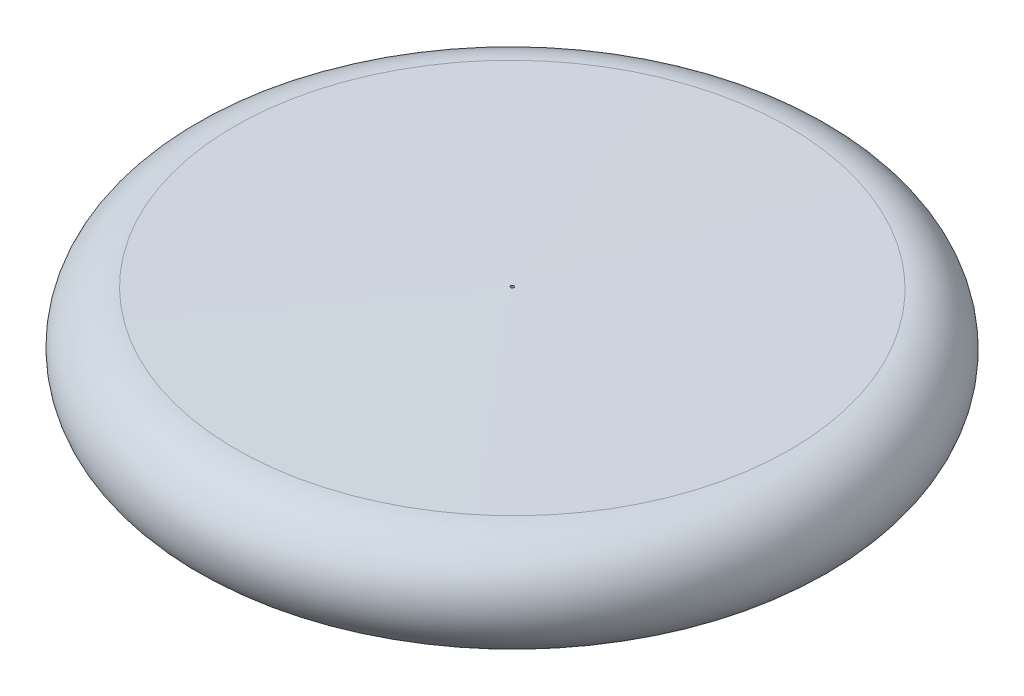
SolidWorks part; units mm, degrees
ref_plane "Front Plane" through (0, 0, 0) normal (0, 0, 1) x (1, 0, 0)
ref_plane "Top Plane" through (0, 0, 0) normal (0, 1, 0) x (1, 0, 0)
ref_plane "Right Plane" through (0, 0, 0) normal (1, 0, 0) x (0, 0, -1)
sketch "Sketch1" plane through (0, 0, 0) normal (0, 0, 1) x (1, 0, 0)
  line L0 (-2.258, 14.3692) -> (30.1083, 14.3692)
  line L1 (30.1083, 14.3692) -> (30.1083, 2.1567)
  line L2 (30.1083, 2.1567) -> (-2.258, 2.1567)
  line L3 (30.291, 14.3692) -> (30.2389, 2.1567) construction
  arc A0 (-2.258, 14.3692) -> (-2.258, 2.1567) centre (-2.258, 8.263) ccw
revolve "Revolve1" add sketch "Sketch1" angle 360 about L3
scale "Scale1" scale about centroid uniform scaling yes scale factor 0.5
scale "Scale2" scale about centroid uniform scaling yes scale factor 0.3
scale "Scale3" scale about centroid uniform scaling yes scale factor 0.5
scale "Scale4" scale about centroid uniform scaling yes scale factor 1
scale "Scale5" scale about centroid uniform scaling yes scale factor 5
